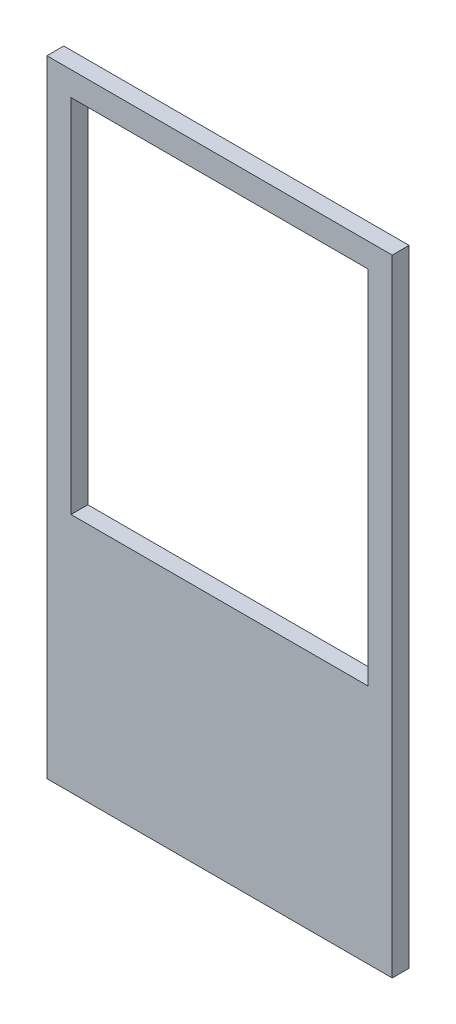
SolidWorks part; units mm, degrees
material "Plain Carbon Steel"
ref_plane "Front Plane" through (0, 0, 0) normal (0, 0, 1) x (1, 0, 0)
ref_plane "Top Plane" through (0, 0, 0) normal (0, 1, 0) x (1, 0, 0)
ref_plane "Right Plane" through (0, 0, 0) normal (1, 0, 0) x (0, 0, -1)
sketch "Sketch2" plane through (0, 0, 0) normal (0, 0, 1) x (1, 0, 0)
  line L0 (-617.01, 1199.72) -> (617.01, 1199.72)
  line L1 (717.01, -1300) -> (-717.01, -1300)
  line L2 (717.01, -1300) -> (717.01, 1300)
  line L3 (717.01, 1300) -> (-717.01, 1300)
  line L4 (-717.01, -1300) -> (-717.01, 1300)
  line L5 (617.01, 1199.72) -> (617.01, -300)
  line L6 (617.01, -300) -> (-617.01, -300)
  line L7 (-617.01, -300) -> (-617.01, 1199.72)
  point P0 (0, 0)
  dimension "D1" = 100
  dimension "D2" = 2600
  dimension "D3" = 1434.02
  dimension "D4" = 100
  dimension "D5" = 100.28
  dimension "D6" = 1000
extrude "Boss-Extrude1" add sketch "Sketch2" along normal blind 70
